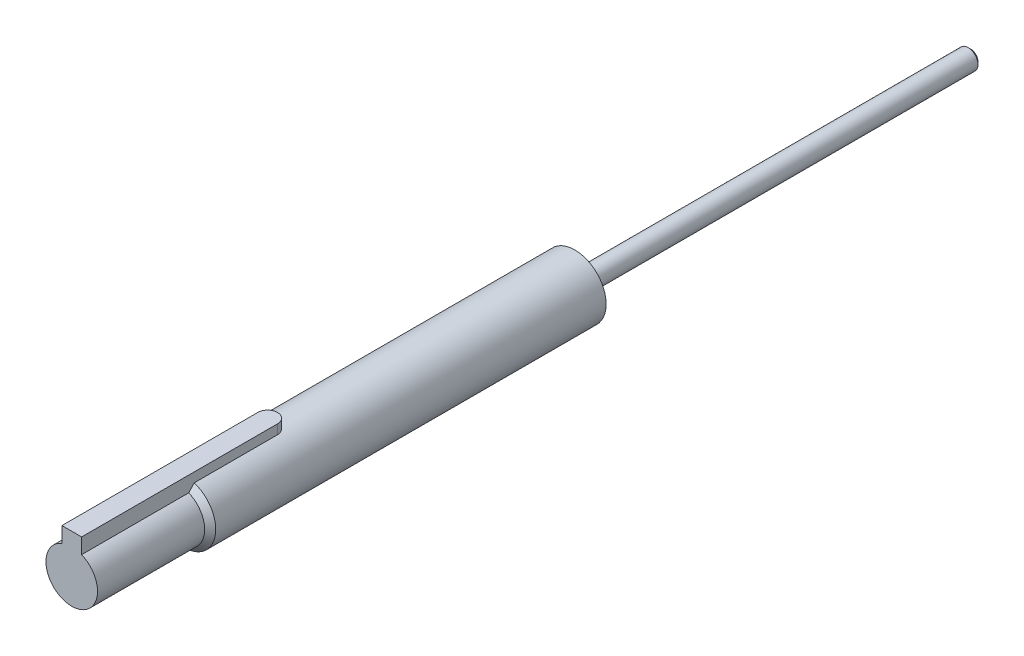
SolidWorks part; units mm, degrees
ref_plane "Front" through (0, 0, 0) normal (0, 0, 1) x (1, 0, 0)
ref_plane "Top" through (0, 0, 0) normal (0, 1, 0) x (1, 0, 0)
ref_plane "Right" through (0, 0, 0) normal (1, 0, 0) x (0, 0, -1)
sketch "Support-Right-Body" plane through (0, 0, 0) normal (1, 0, 0) x (0, 0, -1)
  line L0 (-31.75, 0) -> (169, 0) construction
  line L1 (-31.75, 6.5379) -> (-30.3504, 7.9375)
  line L2 (-31.75, 7.9375) -> (68.625, 7.9375)
  line L3 (-31.75, 7.9375) -> (-31.75, -7.9375)
  line L4 (-31.75, -7.9375) -> (68.625, -7.9375)
  line L5 (169, 2.5) -> (169, -2.5)
  line L6 (-31.75, 7.9375) -> (-31.0502, 7.2377) construction
  line L7 (-30.3504, 7.9375) -> (-31.75, 0) construction
  line L13 (68.625, 7.9375) -> (68.625, -7.9375)
  line L15 (68.625, -2.5) -> (68.625, 2.5)
  line L16 (68.625, 2.5) -> (169, 2.5)
  line L17 (169, -2.5) -> (68.625, -2.5)
  line L18 (168.3301, 2.5) -> (169, 1.8301)
  line L19 (168.6651, 2.1651) -> (169, 2.5) construction
  line L20 (168.3301, 2.5) -> (169, 0) construction
  line L22 (-31.75, 7.9375) -> (-6.75, 7.9375)
  line L23 (-31.75, 7.9375) -> (-31.75, -2.0286)
  line L24 (-31.75, -2.0286) -> (-6.75, -2.0286)
  line L25 (-6.75, 7.9375) -> (-6.75, -2.0286)
  line L27 (-31.75, 7.9375) -> (-31.75, 9.9375)
  line L28 (-31.75, 9.9375) -> (-6.75, 9.9375)
  line L29 (-6.75, 7.9375) -> (-6.75, 9.9375)
  point P3 (156, 0)
  point P5 (169, 0)
  point P9 (-31.75, 0)
  dimension "D1" = 10
  dimension "Length-Front" = 31.75
  dimension "D2" = 15
  dimension "Length" = 156
  dimension "Length-Back" = 13
  dimension "Diam" = 15.875
  dimension "Diam-Back" = 5
  dimension "Length-Slot" = 25
  dimension "Diam-Slot" = 5.9089
  dimension "Diam-Key" = 17.875
sketch "Support-Top-Key" plane through (0, 0, 0) normal (0, 1, 0) x (1, 0, 0)
  line L0 (0, -31.75) -> (0, 169) construction
  line L1 (-2.5, -31.75) -> (2.5, -31.75)
  line L2 (-2.5, -31.75) -> (-2.5, -9.25)
  line L3 (0, -31.75) -> (0, -6.75) construction
  line L4 (2.5, -31.75) -> (2.5, -9.25)
  line L5 (0, -31.75) -> (0, 169) construction
  line L6 (0, -31.75) -> (0, -6.75) construction
  arc A0 (-2.5, -9.25) -> (2.5, -9.25) centre (0, -9.25) cw
  point P6 (0, -31.75)
  dimension "Width-Key" = 5
ref_axis "Ref-Axis-Center" through (0, 0, -80.9) along (0, 0, 1)
ref_plane "Ref-Plane-Key-End" through (0, 9.9375, 0) normal (0, 1, 0) x (-1, 0, 0)
sketch "Sketch3" plane through (0, 0, 0) normal (1, 0, 0) x (0, 0, -1)
  line L0 (-31.75, 0) -> (169, 0) construction
  line L1 (-31.75, 7.9375) -> (-31.75, -7.9375) construction
  line L4 (68.625, 7.9375) -> (68.625, -7.9375) construction
  line L5 (-31.75, 0) -> (68.625, 0)
  line L8 (-31.75, 7.9375) -> (68.625, 7.9375) construction
  line L9 (68.625, 7.9375) -> (68.625, 0)
  line L10 (-31.75, 6.5379) -> (-31.75, 0)
  line L11 (-30.3504, 7.9375) -> (68.625, 7.9375)
  line L12 (-31.75, 6.5379) -> (-30.3504, 7.9375) construction
  line L13 (-31.75, 6.5379) -> (-30.3504, 7.9375)
revolve "Body" add sketch "Sketch3" angle 360 about axis through (0, 0, -80.9) along (0, 0, 1)
sketch "Sketch4" plane through (0, 0, 0) normal (1, 0, 0) x (0, 0, -1)
  line L0 (68.625, -2.5) -> (68.625, 2.5) construction
  line L1 (68.625, 2.5) -> (169, 2.5) construction
  line L2 (-31.75, 0) -> (169, 0) construction
  line L3 (169, 2.5) -> (169, -2.5) construction
  line L4 (168.3301, 2.5) -> (169, 1.8301) construction
  line L5 (68.625, 0) -> (68.625, 2.5)
  line L6 (68.625, 2.5) -> (168.3301, 2.5)
  line L7 (68.625, 0) -> (169, 0)
  line L8 (169, 1.8301) -> (169, 0)
  line L9 (168.3301, 2.5) -> (169, 1.8301)
revolve "Body-Back" add sketch "Sketch4" angle 360 about axis through (0, 0, -80.9) along (0, 0, 1)
sketch "Sketch5" plane through (0, 0, 0) normal (1, 0, 0) x (0, 0, -1)
  line L0 (-31.75, 7.9375) -> (-6.75, 7.9375) construction
  line L1 (-6.75, 7.9375) -> (-6.75, -2.0286) construction
  line L2 (-31.75, -2.0286) -> (-6.75, -2.0286) construction
  line L3 (-31.75, 7.9375) -> (-31.75, -2.0286) construction
  line L4 (-31.75, 7.9375) -> (-6.75, 7.9375)
  line L5 (-6.75, 7.9375) -> (-6.75, -2.0286)
  line L6 (-31.75, -2.0286) -> (-6.75, -2.0286)
  line L7 (-31.75, 7.9375) -> (-31.75, -2.0286)
extrude "Cut-Key" [suppressed] cut sketch "Sketch5" against normal through all and the other way through all
sketch "Sketch7" plane through (0, 0, 0) normal (0, 1, 0) x (1, 0, 0)
  line L3 (-2.5, -31.75) -> (2.5, -31.75)
  line L4 (2.5, -31.75) -> (2.5, -9.25)
  line L5 (-2.5, -9.25) -> (-2.5, -31.75)
  line L6 (-2.5, -31.75) -> (2.5, -31.75)
  line L7 (2.5, -31.75) -> (2.5, -9.25)
  line L8 (-2.5, -9.25) -> (-2.5, -31.75)
  arc A1 (2.5, -9.25) -> (-2.5, -9.25) centre (0, -9.25) ccw
  arc A2 (2.5, -9.25) -> (-2.5, -9.25) centre (0, -9.25) ccw
  dimension "D1" = 0
extrude "Body-Key" add sketch "Sketch7" along normal up to surface (9.9375 mm away) up to plane "Ref-Plane-Key-End"
sketch "Sketch8" plane through (0, 0, 31.75) normal (0, 0, 1) x (1, 0, 0)
  line L0 (-2.5, 9.9375) -> (-2.5, 6.041) construction
  line L2 (2.5, 6.041) -> (2.5, 9.9375)
  line L3 (2.5, 9.9375) -> (-2.5, 9.9375)
  line L4 (-2.5, 6.041) -> (-2.5, 9.9375)
  line L5 (-2.5, 9.9375) -> (2.5, 9.9375) construction
  arc A0 (-2.5, 6.041) -> (2.5, 6.041) centre (0, 0) ccw
extrude "Boss-Extrude1" add sketch "Sketch8" along normal blind 27.16
